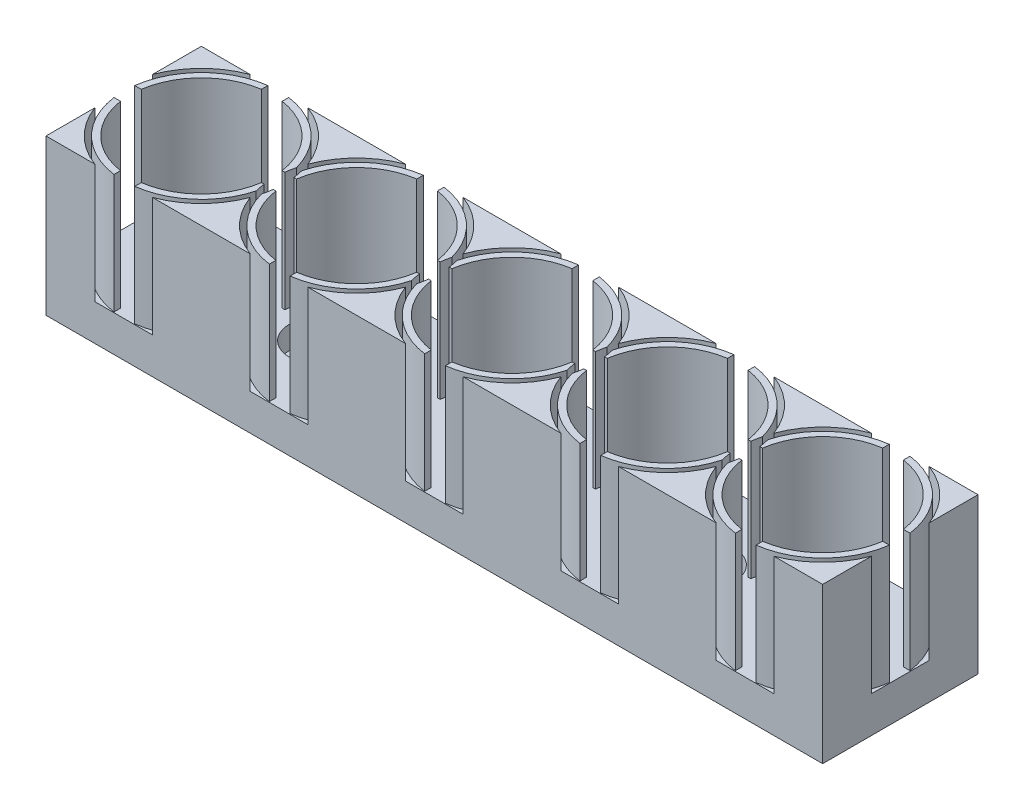
SolidWorks part; units mm, degrees
ref_plane "Front Plane" through (0, 0, 0) normal (0, 0, 1) x (1, 0, 0)
ref_plane "Top Plane" through (0, 0, 0) normal (0, 1, 0) x (1, 0, 0)
ref_plane "Right Plane" through (0, 0, 0) normal (1, 0, 0) x (0, 0, -1)
sketch "Sketch2" plane through (0, 0, 0) normal (0, 1, 0) x (1, 0, 0)
  line L1 (-75, 15) -> (75, 15)
  line L2 (-75, 15) -> (-75, -15)
  line L3 (-75, -15) -> (75, -15)
  line L4 (75, 15) -> (75, -15)
  line L5 (-75, 15) -> (75, -15) construction
  line L6 (-75, -15) -> (75, 15) construction
  point P0 (0, 0)
  dimension "D1" = 150
  dimension "D2" = 30
extrude "Boss-Extrude1" add sketch "Sketch2" along normal blind 30
sketch "Sketch3" plane through (0, 30, 0) normal (0, 1, 0) x (1, 0, 0)
  line L0 (-75, 15) -> (-75, -15) construction
  line L1 (75, 15) -> (-75, 15) construction
  circle A0 centre (-60, 0) radius 13.75
  dimension "D3" = 27.5
  dimension "D1" = 15
  dimension "D2" = 15
extrude "Cut-Extrude1" cut sketch "Sketch3" against normal blind 23
pattern_linear "LPattern1" count 5 spacing 30 along (1, 0, 0) of "Cut-Extrude1"
hole_wizard "CBORE for M4 Hex Socket Head Cap Screw1" positions "Sketch6" profile "Sketch5" counterbore size "M4" standard "DIN" end condition through all
sketch "Sketch6" plane through (0, 7, 0) normal (0, 1, 0) x (-1, 0, 0)
  circle A0 centre (60, 0) radius 13.75 construction
  point P0 (60, 0)
  dimension "D2" = 0
  dimension "D1" = 0
sketch "Sketch5" plane through (-60, 7, 0) normal (1, 0, 0) x (0, 0, 1)
  line L0 (0, 0) -> (0, 7)
  line L1 (0, 7) -> (2.25, 7)
  line L3 (2.25, 7) -> (2.25, 4.4)
  line L4 (2.25, 4.4) -> (4, 4.4)
  line L5 (4, 4.4) -> (4, 0)
  line L7 (4, 0) -> (0, 0)
  line L11 (0, -6.35) -> (0, 107.95) construction
  dimension "Thru Hole Dia." = 4.5
  dimension "Thru Hole Depth" = 7
  dimension "C'Bore Dia." = 8
  dimension "C'Bore Depth" = 4.4
pattern_linear "LPattern2" count 2 spacing 120 along (1, 0, 0) of "CBORE for M4 Hex Socket Head Cap Screw1"
sketch "Sketch7" plane through (0, 30, 0) normal (0, 1, 0) x (1, 0, 0)
  line L1 (-90.5645, -2) -> (90.5645, -2)
  line L2 (-90.5645, -2) -> (-90.5645, 2)
  line L3 (-90.5645, 2) -> (90.5645, 2)
  line L4 (90.5645, -2) -> (90.5645, 2)
  line L5 (-90.5645, -2) -> (90.5645, 2) construction
  line L6 (-90.5645, 2) -> (90.5645, -2) construction
  point P0 (0, 0)
  dimension "D1" = 4
extrude "Cut-Extrude3" cut sketch "Sketch7" against normal blind 23
sketch "Sketch8" plane through (0, 30, 0) normal (0, 1, 0) x (-1, 0, 0)
  line L1 (62, -26.2987) -> (58, -26.2987)
  line L2 (62, -26.2987) -> (62, 23.7013)
  line L3 (62, 23.7013) -> (58, 23.7013)
  line L4 (58, -26.2987) -> (58, 23.7013)
  line L5 (62, -26.2987) -> (58, 23.7013) construction
  line L6 (62, 23.7013) -> (58, -26.2987) construction
  circle A0 centre (60, 0) radius 13.75 construction
  point P0 (60, -1.2987)
  dimension "D1" = 4
  dimension "D2" = 50
  dimension "D3" = 0
extrude "Cut-Extrude4" cut sketch "Sketch8" against normal blind 23
sketch "Skizze1" plane through (0, 7, 0) normal (0, 1, 0) x (-1, 0, 0)
  circle A0 centre (60, 0) radius 15
  circle A1 centre (60, 0) radius 16
extrude "Schnitt-Linear austragen1" cut sketch "Skizze1" along normal through all
pattern_linear "LPattern3" count 5 spacing 30 along (1, 0, 0) of "Cut-Extrude4", "Schnitt-Linear austragen1"
hole_wizard "CBORE for M6 Hex Socket Head Cap Screw1" positions "Sketch10" profile "Sketch9" counterbore size "M6" standard "DIN" end condition through all
sketch "Sketch10" plane through (0, 7, 0) normal (0, 1, 0) x (-1, 0, 0)
  line L0 (75, -15) -> (75, 15) construction
  arc A0 (32, -13.6038) -> (43.6038, -2) centre (30, 0) ccw construction
  point P0 (37.5, 0)
  point P2 (75, 0)
  dimension "D1" = 0
  dimension "D2" = 7.5
sketch "Sketch9" plane through (-37.5, 7, 0) normal (1, 0, 0) x (0, 0, 1)
  line L0 (0, 0) -> (0, 7)
  line L1 (0, 7) -> (3.3, 7)
  line L3 (3.3, 7) -> (3.3, 4.4)
  line L4 (3.3, 4.4) -> (5.5, 4.4)
  line L5 (5.5, 4.4) -> (5.5, 0)
  line L7 (5.5, 0) -> (0, 0)
  line L11 (0, -6.35) -> (0, 107.95) construction
  dimension "Thru Hole Dia." = 6.6
  dimension "Thru Hole Depth" = 7
  dimension "C'Bore Dia." = 11
  dimension "C'Bore Depth" = 4.4
pattern_linear "LPattern4" count 2 spacing 75 along (1, 0, 0) of "CBORE for M6 Hex Socket Head Cap Screw1"
